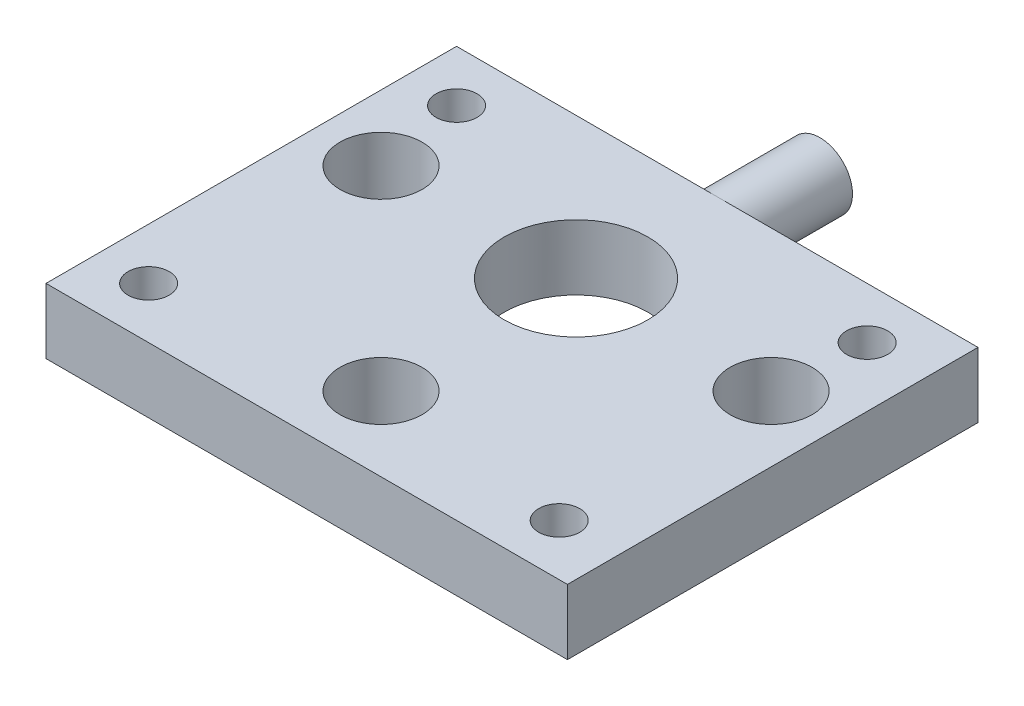
SolidWorks part; units mm, degrees
ref_plane "Alzado" through (0, 0, 0) normal (0, 0, 1) x (1, 0, 0)
ref_plane "Planta" through (0, 0, 0) normal (0, 1, 0) x (1, 0, 0)
ref_plane "Vista lateral" through (0, 0, 0) normal (1, 0, 0) x (0, 0, -1)
sketch "Croquis1" plane through (0, 0, 0) normal (0, 1, 0) x (1, 0, 0)
  line L1 (-25.4, 40) -> (25.4, 40)
  line L2 (-25.4, 40) -> (-25.4, -40)
  line L3 (-25.4, -40) -> (25.4, -40)
  line L4 (25.4, 40) -> (25.4, -40)
  line L5 (-25.4, 40) -> (25.4, -40) construction
  line L6 (-25.4, -40) -> (25.4, 40) construction
  point P0 (0, 0)
  dimension "D1" = 80
  dimension "D2" = 50.8
extrude "Saliente-Extruir1" add sketch "Croquis1" along normal blind 6.35
sketch "Croquis4" plane through (0, 6.35, 0) normal (0, 1, 0) x (1, 0, 0)
  circle A0 centre (-19, 19.4661) radius 4
  circle A1 centre (19, 19.4661) radius 4
  circle A2 centre (0, 0.4661) radius 4
  dimension "D3" = 8
  dimension "D5" = 8
  dimension "D4" = 8
  dimension "D1" = 38
  dimension "D2" = 19
  dimension "D6" = 19
extrude "Cortar-Extruir3" cut sketch "Croquis4" against normal through all
sketch "Croquis5" plane through (0, 6.35, 0) normal (0, 1, 0) x (1, 0, 0)
  line L0 (25.4, -40) -> (25.4, 40) construction
  line L1 (-25.4, -40) -> (25.4, -40)
  line L2 (-25.4, -40) -> (-25.4, -27.3)
  line L3 (-25.4, -27.3) -> (25.4, -27.3)
  line L4 (25.4, -40) -> (25.4, -27.3)
  dimension "D1" = 12.7
extrude "Cortar-Extruir4" cut sketch "Croquis5" against normal through all
sketch "Croquis6" plane through (0, 6.35, 0) normal (0, 1, 0) x (1, 0, 0)
  line L0 (25.4, -27.3) -> (25.4, 40) construction
  line L1 (-25.4, -27.3) -> (25.4, -27.3)
  line L2 (-25.4, -27.3) -> (-25.4, -6.7734)
  line L3 (-25.4, -6.7734) -> (25.4, -6.7734)
  line L4 (25.4, -27.3) -> (25.4, -6.7734)
extrude "Cortar-Extruir5" cut sketch "Croquis6" against normal blind 10
sketch "Croquis7" plane through (0, 0, 0) normal (0, -1, 0) x (1, 0, 0)
  line L0 (25.4, 6.7734) -> (25.4, -40) construction
  line L1 (-25.4, 6.7734) -> (25.4, 6.7734)
  line L2 (-25.4, 6.7734) -> (-25.4, -33.2266)
  line L3 (-25.4, -33.2266) -> (25.4, -33.2266)
  line L4 (25.4, 6.7734) -> (25.4, -33.2266)
  line L6 (-25.4, -33.2266) -> (25.4, -33.2266)
  line L7 (-25.4, -33.2266) -> (-25.4, -40)
  line L8 (-25.4, -40) -> (25.4, -40)
  line L9 (25.4, -33.2266) -> (25.4, -40)
  line M5 (25.4, -40) -> (25.4, 6.7734)
  line M7 (-25.4, 6.7734) -> (-25.4, -40)
  line M8 (-25.4, -40) -> (25.4, -40)
  dimension "D1" = 40
extrude "Cortar-Extruir6" cut sketch "Croquis7" against normal blind 10 contours L3 M7 M8 M5
sketch "Croquis8" plane through (0, 0, -33.2266) normal (0, 0, -1) x (-1, 0, 0)
  circle A0 centre (0, 3.175) radius 3.175
extrude "Saliente-Extruir2" add sketch "Croquis8" along normal blind 10
sketch "Croquis9" plane through (0, 0, 0) normal (0, -1, 0) x (1, 0, 0)
  line L0 (-19, -19.4661) -> (19, -19.4661) construction
  circle A0 centre (0, -19.4661) radius 7
  dimension "D1" = 14
extrude "Cortar-Extruir7" cut sketch "Croquis9" against normal blind 10
sketch "Croquis10" plane through (0, 0, 0) normal (0, -1, 0) x (1, 0, 0)
  line L0 (25.4, 6.7734) -> (-25.4, 6.7734) construction
  line L1 (-25.4, -33.2266) -> (-25.4, 6.7734) construction
  circle A0 centre (-20.4, 1.7734) radius 2
  circle A1 centre (19.6, 1.7734) radius 2
  circle A2 centre (19.6, -28.2266) radius 2
  circle A3 centre (-20.4, -28.2266) radius 2
  dimension "D1" = 4
  dimension "D2" = 5
  dimension "D3" = 5
  dimension "D4" = 2
  dimension "D5" = 2
extrude "Cortar-Extruir8" cut sketch "Croquis10" against normal blind 10
equation "\"D2@Croquis4\"=\"D1@Croquis4\"/2"
equation "\"D5@Croquis4\"=\"D3@Croquis4\""
equation "\"D4@Croquis4\"=\"D3@Croquis4\""
